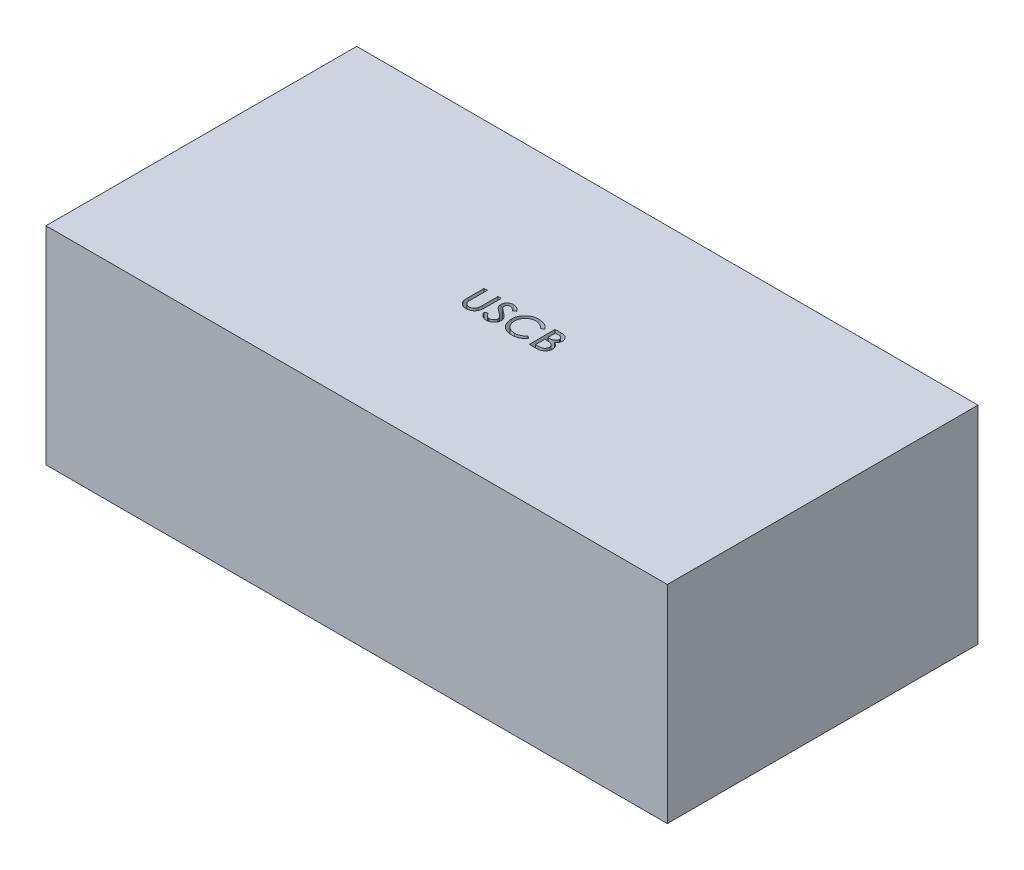
SolidWorks part; units mm, degrees
ref_plane "Front Plane" through (0, 0, 0) normal (0, 0, 1) x (1, 0, 0)
ref_plane "Top Plane" through (0, 0, 0) normal (0, 1, 0) x (1, 0, 0)
ref_plane "Right Plane" through (0, 0, 0) normal (1, 0, 0) x (0, 0, -1)
sketch "Sketch1" plane through (0, 0, 0) normal (0, 1, 0) x (1, 0, 0)
  line L1 (-38.1, -19.05) -> (38.1, -19.05)
  line L2 (-38.1, -19.05) -> (-38.1, 19.05)
  line L3 (-38.1, 19.05) -> (38.1, 19.05)
  line L4 (38.1, -19.05) -> (38.1, 19.05)
  line L5 (-38.1, -19.05) -> (38.1, 19.05) construction
  line L6 (-38.1, 19.05) -> (38.1, -19.05) construction
  point P0 (0, 0)
  dimension "D1" = 76.2
  dimension "D2" = 38.1
extrude "Boss-Extrude1" add sketch "Sketch1" along normal blind 25.4
sketch "Sketch2" plane through (0, 25.4, 0) normal (0, 1, 0) x (1, 0, 0)
  text T0 "<b>USCB</b>" font "Century Gothic" height 3.175
  point P1 (-26.9782, 3.5439)
  point P2 (-7.3188, -1.6376)
  point P3 (-2.4478, -2.0172)
extrude "Cut-Extrude1" cut sketch "Sketch2" against normal through all
